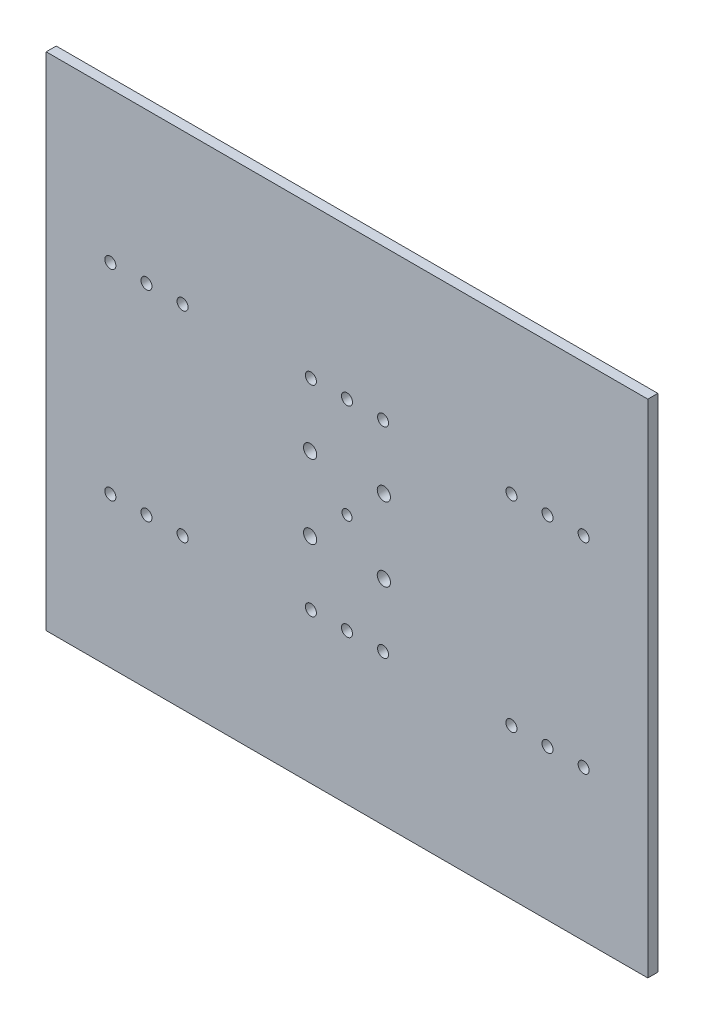
SolidWorks part; units mm, degrees
ref_plane "前视基准面" through (0, 0, 0) normal (0, 0, 1) x (1, 0, 0)
ref_plane "上视基准面" through (0, 0, 0) normal (0, 1, 0) x (1, 0, 0)
ref_plane "右视基准面" through (0, 0, 0) normal (1, 0, 0) x (0, 0, -1)
sketch "草图1" plane through (0, 0, 0) normal (0, 0, 1) x (1, 0, 0)
  line L0 (-18.3848, 18.3848) -> (0, 0) construction
  line L1 (150, -125) -> (-150, -125)
  line L2 (150, -125) -> (150, 125)
  line L3 (150, 125) -> (-150, 125)
  line L4 (-150, -125) -> (-150, 125)
  line L5 (150, -125) -> (-150, 125) construction
  line L6 (150, 125) -> (-150, -125) construction
  line L7 (0, 0) -> (0, 75.2853) construction
  line L8 (0, 0) -> (89.5261, 0) construction
  circle A0 centre (-18.3848, 18.3848) radius 3.3
  circle A1 centre (18.3848, 18.3848) radius 3.3
  circle A2 centre (18.3848, -18.3848) radius 3.3
  circle A3 centre (-18.3848, -18.3848) radius 3.3
  circle A4 centre (0, 0) radius 2.5
  point P0 (0, 0)
  dimension "D3" = 6.6
  dimension "D6" = 5
  dimension "D1" = 250
  dimension "D2" = 300
  dimension "D4" = 26
  dimension "D5" = 45
extrude "凸台-拉伸1" add sketch "草图1" along normal blind 5
sketch "草图2" plane through (0, 0, 5) normal (0, 0, 1) x (1, 0, 0)
  line L0 (-150, 0) -> (150, 0) construction
  line L1 (-150, 125) -> (-150, -125) construction
  line L2 (150, -125) -> (150, 125) construction
  line L3 (0, 125) -> (0, -125) construction
  line L4 (150, 125) -> (-150, 125) construction
  line L5 (-150, -125) -> (150, -125) construction
  line L7 (100, -50) -> (-100, -50) construction
  line L8 (100, -50) -> (100, 50) construction
  line L9 (100, 50) -> (-100, 50) construction
  line L10 (-100, -50) -> (-100, 50) construction
  line L11 (100, -50) -> (-100, 50) construction
  line L12 (100, 50) -> (-100, -50) construction
  circle A0 centre (-100, 50) radius 2.75
  circle A1 centre (0, 50) radius 2.75
  circle A2 centre (100, 50) radius 2.75
  circle A3 centre (100, -50) radius 2.75
  circle A4 centre (0, -50) radius 2.75
  circle A5 centre (-100, -50) radius 2.75
  circle A6 centre (-118, 50) radius 2.75
  circle A7 centre (-82, 50) radius 2.75
  circle A8 centre (-82, -50) radius 2.75
  circle A9 centre (-118, -50) radius 2.75
  circle A10 centre (-18, 50) radius 2.75
  circle A11 centre (-18, -50) radius 2.75
  circle A12 centre (118, -50) radius 2.75
  circle A13 centre (82, -50) radius 2.75
  circle A14 centre (18, -50) radius 2.75
  circle A15 centre (18, 50) radius 2.75
  circle A16 centre (82, 50) radius 2.75
  circle A17 centre (118, 50) radius 2.75
  point P12 (0, 0)
  point P26 (-118, 50)
  dimension "D1" = 5.5
  dimension "D4" = 5.5
  dimension "D6" = 5.5
  dimension "D7" = 18
  dimension "D2" = 100
  dimension "D3" = 200
  dimension "D5" = 18
extrude "切除-拉伸1" cut sketch "草图2" against normal through all
